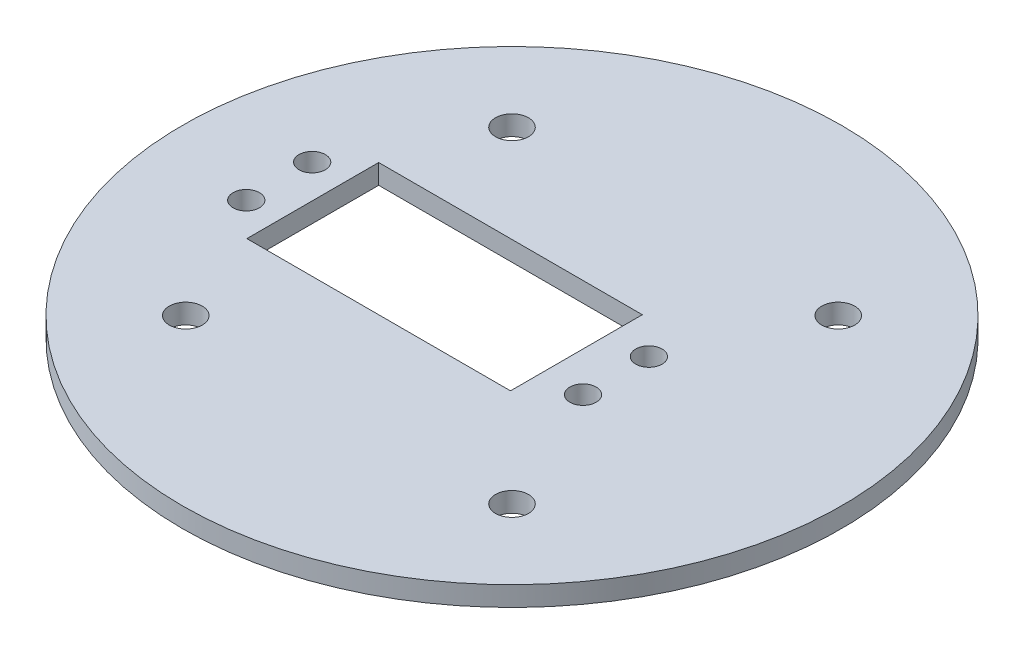
SolidWorks part; units mm, degrees
material "Oak"
ref_plane "Front Plane" through (0, 0, 0) normal (0, 0, 1) x (1, 0, 0)
ref_plane "Top Plane" through (0, 0, 0) normal (0, 1, 0) x (1, 0, 0)
ref_plane "Right Plane" through (0, 0, 0) normal (1, 0, 0) x (0, 0, -1)
sketch "Sketch2" plane through (0, 0, 0) normal (0, 1, 0) x (1, 0, 0)
  line L0 (0, -50) -> (0, 50) construction
  line L5 (-50, 0) -> (50, 0) construction
  line L6 (-35.3553, -35.3553) -> (35.3553, 35.3553) construction
  line L7 (35.3553, -35.3553) -> (-35.3553, 35.3553) construction
  line L8 (15.7721, -10) -> (15.7721, 10) construction
  line L9 (-9.7721, -10) -> (9.7721, -10)
  line L11 (-9.7721, 10) -> (9.7721, 10)
  line L12 (9.7721, -10) -> (9.7721, 10)
  line L13 (-9.7721, -10) -> (9.7721, 10) construction
  line L14 (-9.7721, 10) -> (9.7721, -10) construction
  line L15 (-9.7721, -10) -> (-30.2279, -10)
  line L17 (-9.7721, 10) -> (-30.2279, 10)
  line L18 (-30.2279, -10) -> (-30.2279, 10)
  line L19 (-9.7721, 10) -> (-9.7721, -10) construction
  circle A0 centre (0, 0) radius 50
  circle A7 centre (-24.7487, 24.7487) radius 2.5
  circle A8 centre (24.7487, 24.7487) radius 2.5
  circle A9 centre (24.7487, -24.7487) radius 2.5
  circle A10 centre (-24.7487, -24.7487) radius 2.5
  circle A11 centre (15.7721, 5) radius 2
  circle A12 centre (15.7721, -5) radius 2
  circle A13 centre (-35.3162, -5) radius 2
  circle A14 centre (-35.3162, 5) radius 2
  point P5 (0, 0)
  point P9 (0, 0)
  point P11 (0, 0)
  point P15 (0, 0)
  point P26 (0, 0)
  dimension "D1" = 45
  dimension "D2" = 45
  dimension "D6" = 20
  dimension "D3" = 100
  dimension "D4" = 35
  dimension "D8" = 4
  dimension "D9" = 5
  dimension "D5" = 6
  dimension "D7" = 40
extrude "Boss-Extrude1" add sketch "Sketch2" along normal blind 3
